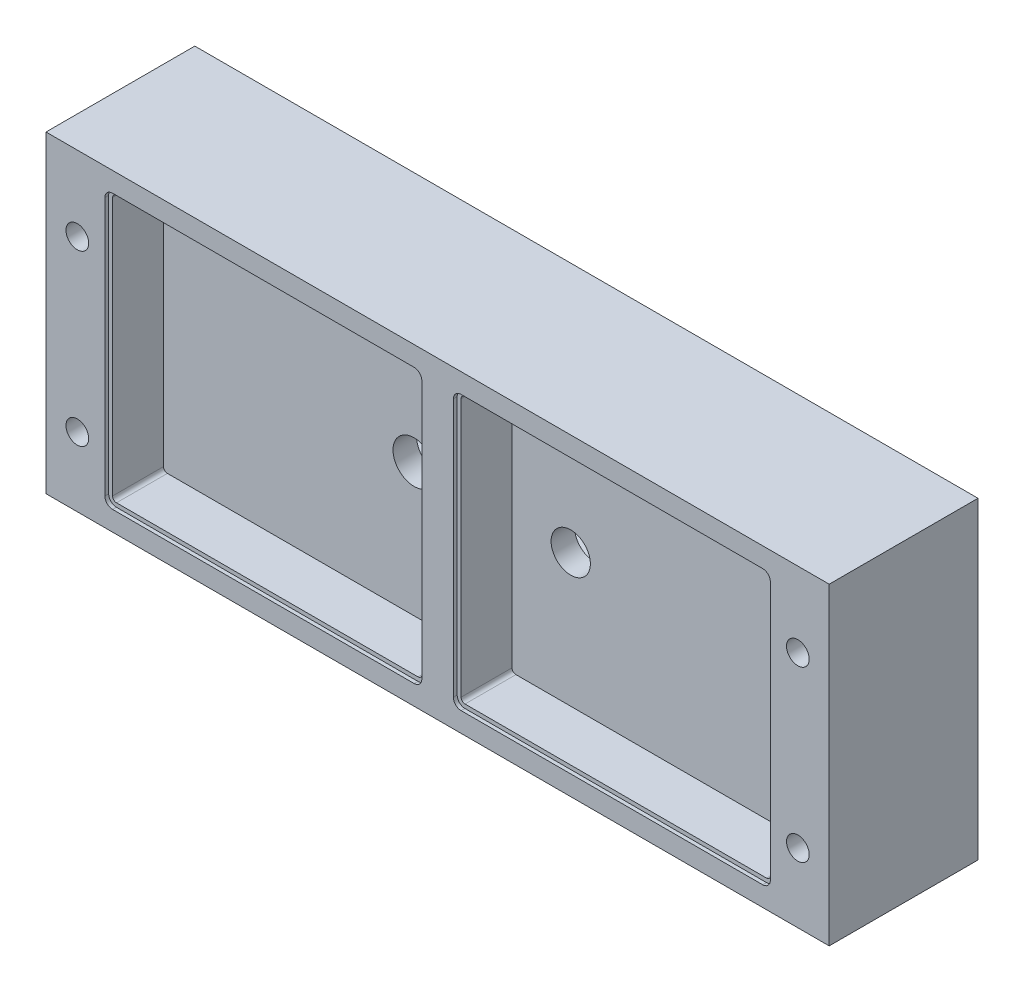
SolidWorks part; units mm, degrees
ref_plane "Front Plane" through (0, 0, 0) normal (0, 0, 1) x (1, 0, 0)
ref_plane "Top Plane" through (0, 0, 0) normal (0, 1, 0) x (1, 0, 0)
ref_plane "Right Plane" through (0, 0, 0) normal (1, 0, 0) x (0, 0, -1)
sketch "Sketch1" plane through (0, 0, 0) normal (0, 0, 1) x (1, 0, 0)
  line L1 (-33.75, 21.5625) -> (66.25, 21.5625)
  line L2 (-33.75, 21.5625) -> (-33.75, -18.4375)
  line L3 (-33.75, -18.4375) -> (66.25, -18.4375)
  line L4 (66.25, 21.5625) -> (66.25, -18.4375)
  dimension "D1" = 100
  dimension "D2" = 40
extrude "Boss-Extrude1" add sketch "Sketch1" along normal blind 38
sketch "Sketch2" plane through (0, 0, 0) normal (0, 0, -1) x (-1, 0, 0)
  line L0 (-66.25, -18.4375) -> (-66.25, 21.5625) construction
  line L1 (-58.25, 18.5625) -> (-18.75, 18.5625)
  line L2 (-58.25, 18.5625) -> (-58.25, -15.4375)
  line L3 (-58.25, -15.4375) -> (-18.75, -15.4375)
  line L4 (-18.75, 18.5625) -> (-18.75, -15.4375)
  line L5 (-13.75, 18.5625) -> (25.75, 18.5625)
  line L6 (-13.75, 18.5625) -> (-13.75, -15.4375)
  line L7 (-13.75, -15.4375) -> (25.75, -15.4375)
  line L8 (25.75, 18.5625) -> (25.75, -15.4375)
  line L9 (33.75, 21.5625) -> (33.75, -18.4375) construction
  line L10 (-66.25, 21.5625) -> (33.75, 21.5625) construction
  line L11 (33.75, -18.4375) -> (-66.25, -18.4375) construction
  dimension "D1" = 8
  dimension "D2" = 8
  dimension "D3" = 5
  dimension "D4" = 3
  dimension "D5" = 3
  dimension "D6" = 3
  dimension "D7" = 3
  dimension "D8" = 39.5
  dimension "D9" = 39.5
extrude "Cut-Extrude2" cut sketch "Sketch2" against normal blind 21 from offset 12 offset against normal yes
sketch "Sketch4" plane through (0, 0, 0) normal (0, 0, -1) x (-1, 0, 0)
  line L0 (-66.25, -18.4375) -> (-66.25, 21.5625) construction
  line L1 (33.75, 21.5625) -> (33.75, -18.4375) construction
  circle A0 centre (-62.25, 11.9848) radius 1.45
  circle A1 centre (-62.25, -9.6166) radius 1.45
  circle A2 centre (29.75, 11.9848) radius 1.45
  circle A3 centre (29.75, -9.6166) radius 1.45
  dimension "D1" = 4
  dimension "D2" = 4
extrude "Cut-Extrude4" cut sketch "Sketch4" against normal up to next
sketch "Sketch6" plane through (0, 21.5625, 0) normal (0, 1, 0) x (1, 0, 0)
  line L0 (-33.75, -38) -> (-33.75, 0) construction
  line L1 (66.25, -38) -> (-33.75, -38)
  line L2 (66.25, -38) -> (66.25, -19)
  line L3 (66.25, -19) -> (-33.75, -19)
  line L4 (-33.75, -38) -> (-33.75, -19)
extrude "Cut-Extrude5" cut sketch "Sketch6" against normal through all
fillet "Fillet1" radius 0.5 8 edges at (58.25, 18.5625, 15.5) (58.25, -15.4375, 15.5) (18.75, -15.4375, 15.5) (18.75, 18.5625, 15.5) (13.75, 18.5625, 15.5) (13.75, -15.4375, 15.5) (-25.75, -15.4375, 15.5) (-25.75, 18.5625, 15.5)
sketch "Sketch10" plane through (0, 0, 12) normal (0, 0, 1) x (1, 0, 0)
  line L8 (14.25, -14.9375) -> (14.25, 18.0625)
  line L9 (13.25, 19.0625) -> (-25.25, 19.0625)
  line L10 (-26.25, 18.0625) -> (-26.25, -14.9375)
  line L11 (-25.25, -15.9375) -> (13.25, -15.9375)
  line L12 (14.25, -14.9375) -> (14.25, 18.0625)
  line L13 (13.25, 19.0625) -> (-25.25, 19.0625)
  line L14 (-26.25, 18.0625) -> (-26.25, -14.9375)
  line L15 (-25.25, -15.9375) -> (13.25, -15.9375)
  arc A8 (14.25, 18.0625) -> (13.25, 19.0625) centre (13.25, 18.0625) ccw
  arc A9 (-25.25, 19.0625) -> (-26.25, 18.0625) centre (-25.25, 18.0625) ccw
  arc A10 (-26.25, -14.9375) -> (-25.25, -15.9375) centre (-25.25, -14.9375) ccw
  arc A11 (13.25, -15.9375) -> (14.25, -14.9375) centre (13.25, -14.9375) ccw
  arc A12 (14.25, 18.0625) -> (13.25, 19.0625) centre (13.25, 18.0625) ccw
  arc A13 (-25.25, 19.0625) -> (-26.25, 18.0625) centre (-25.25, 18.0625) ccw
  arc A14 (-26.25, -14.9375) -> (-25.25, -15.9375) centre (-25.25, -14.9375) ccw
  arc A15 (13.25, -15.9375) -> (14.25, -14.9375) centre (13.25, -14.9375) ccw
  dimension "D1" = 0.5
extrude "Cut-Extrude6" cut sketch "Sketch10" along normal blind 0.5 draft 2 from offset 6.5
sketch "Sketch11" plane through (0, 0, 12) normal (0, 0, 1) x (1, 0, 0)
  line L8 (58.75, -14.9375) -> (58.75, 18.0625)
  line L9 (57.75, 19.0625) -> (19.25, 19.0625)
  line L10 (18.25, 18.0625) -> (18.25, -14.9375)
  line L11 (19.25, -15.9375) -> (57.75, -15.9375)
  line L12 (58.75, -14.9375) -> (58.75, 18.0625)
  line L13 (57.75, 19.0625) -> (19.25, 19.0625)
  line L14 (18.25, 18.0625) -> (18.25, -14.9375)
  line L15 (19.25, -15.9375) -> (57.75, -15.9375)
  arc A8 (58.75, 18.0625) -> (57.75, 19.0625) centre (57.75, 18.0625) ccw
  arc A9 (19.25, 19.0625) -> (18.25, 18.0625) centre (19.25, 18.0625) ccw
  arc A10 (18.25, -14.9375) -> (19.25, -15.9375) centre (19.25, -14.9375) ccw
  arc A11 (57.75, -15.9375) -> (58.75, -14.9375) centre (57.75, -14.9375) ccw
  arc A12 (58.75, 18.0625) -> (57.75, 19.0625) centre (57.75, 18.0625) ccw
  arc A13 (19.25, 19.0625) -> (18.25, 18.0625) centre (19.25, 18.0625) ccw
  arc A14 (18.25, -14.9375) -> (19.25, -15.9375) centre (19.25, -14.9375) ccw
  arc A15 (57.75, -15.9375) -> (58.75, -14.9375) centre (57.75, -14.9375) ccw
  dimension "D1" = 0.5
extrude "Cut-Extrude7" cut sketch "Sketch11" along normal blind 0.5 draft 2 from offset 6.5
sketch "Sketch17" plane through (0, 0, 0) normal (0, 0, -1) x (-1, 0, 0)
  line L0 (-66.25, 1.5625) -> (33.75, 1.5625) construction
  line L3 (-16.25, 21.5625) -> (-16.25, -18.4375) construction
  line L4 (-66.25, 21.5625) -> (33.75, 21.5625) construction
  line L5 (33.75, -18.4375) -> (-66.25, -18.4375) construction
  line L6 (-66.25, -18.4375) -> (-66.25, 21.5625) construction
  line L9 (33.75, 21.5625) -> (33.75, -18.4375) construction
  line L10 (-56.25, 1.5625) -> (23.75, 1.5625) construction
  line L11 (-56.25, 9.0625) -> (23.75, 9.0625)
  line L12 (-56.25, -5.9375) -> (23.75, -5.9375)
  arc A2 (-56.25, 9.0625) -> (-56.25, -5.9375) centre (-56.25, 1.5625) ccw
  arc A3 (23.75, -5.9375) -> (23.75, 9.0625) centre (23.75, 1.5625) ccw
  point P15 (-16.25, 1.5625)
extrude "Cut-Extrude12" cut sketch "Sketch17" against normal blind 9
sketch "Sketch18" plane through (0, 0, 9) normal (0, 0, -1) x (-1, 0, 0)
  line L0 (-66.25, 1.5625) -> (33.75, 1.5625) construction
  line L1 (-66.25, -18.4375) -> (-66.25, 21.5625) construction
  line L2 (33.75, 21.5625) -> (33.75, -18.4375) construction
  line L3 (-16.25, 21.5625) -> (-16.25, -18.4375) construction
  line L4 (-66.25, 21.5625) -> (33.75, 21.5625) construction
  line L5 (33.75, -18.4375) -> (-66.25, -18.4375) construction
  circle A0 centre (-26.25, 1.5625) radius 2.5069
  circle A1 centre (-6.25, 1.5625) radius 2.6931
  dimension "D1" = 20
  dimension "D2" = 10
  dimension "D3" = 10
extrude "Cut-Extrude13" cut sketch "Sketch18" against normal up to next
sketch "Sketch19" plane through (0, 0, 9) normal (0, 0, -1) x (-1, 0, 0)
  circle A0 centre (-26.25, 1.5625) radius 4.572
  circle A1 centre (-26.25, 1.5625) radius 6.477
  circle A2 centre (-6.25, 1.5625) radius 4.572
  circle A3 centre (-6.25, 1.5625) radius 6.477
  dimension "D1" = 9.144
  dimension "D2" = 12.954
  dimension "D3" = 12.954
  dimension "D4" = 9.144
extrude "Cut-Extrude14" cut sketch "Sketch19" against normal blind 0.7937 contours A1 A0 | A3 A2
